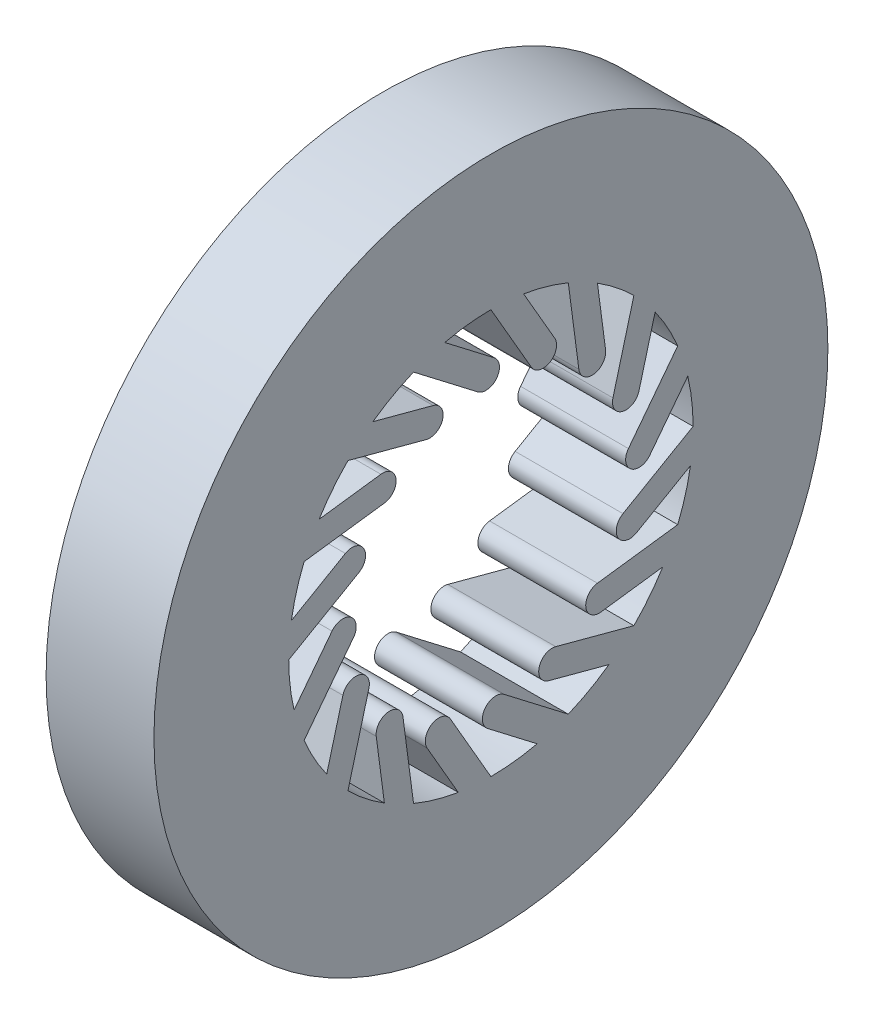
SolidWorks part; units mm, degrees
material "ABS"
ref_plane "Front Plane" through (0, 0, 0) normal (0, 0, 1) x (1, 0, 0)
ref_plane "Top Plane" through (0, 0, 0) normal (0, 1, 0) x (1, 0, 0)
ref_plane "Right Plane" through (0, 0, 0) normal (1, 0, 0) x (0, 0, -1)
sketch "Sketch1" plane through (0, 0, 0) normal (1, 0, 0) x (0, 0, -1)
  line L0 (0, 15) -> (3.0041, 9.7967)
  line L1 (0, -1000) -> (0, 49000) construction
  line L2 (4.7362, 10.7967) -> (2.4231, 14.803)
  line L3 (8.5074, 8.1624) -> (7.9036, 12.7489)
  line L4 (5.7403, 13.8582) -> (6.5245, 7.9013)
  line L5 (10.9834, 4.2854) -> (12.1807, 8.7539)
  line L6 (10.6066, 10.6066) -> (9.0515, 4.8031)
  line L7 (11.7873, -0.2439) -> (14.6035, 3.4262)
  line L8 (13.8582, 5.7403) -> (10.2006, 0.9736)
  line L9 (10.7967, -4.7362) -> (14.803, -2.4231)
  line L10 (15, 0) -> (9.7967, -3.0041)
  line L11 (8.1624, -8.5074) -> (12.7489, -7.9036)
  line L12 (13.8582, -5.7403) -> (7.9013, -6.5245)
  line L13 (4.2854, -10.9834) -> (8.7539, -12.1807)
  line L14 (10.6066, -10.6066) -> (4.8031, -9.0515)
  line L15 (-0.2439, -11.7873) -> (3.4262, -14.6035)
  line L16 (5.7403, -13.8582) -> (0.9736, -10.2006)
  line L17 (-4.7362, -10.7967) -> (-2.4231, -14.803)
  line L18 (0, -15) -> (-3.0041, -9.7967)
  line L19 (-8.5074, -8.1624) -> (-7.9036, -12.7489)
  line L20 (-5.7403, -13.8582) -> (-6.5245, -7.9013)
  line L21 (-10.9834, -4.2854) -> (-12.1807, -8.7539)
  line L22 (-10.6066, -10.6066) -> (-9.0515, -4.8031)
  line L23 (-11.7873, 0.2439) -> (-14.6035, -3.4262)
  line L24 (-13.8582, -5.7403) -> (-10.2006, -0.9736)
  line L25 (-10.7967, 4.7362) -> (-14.803, 2.4231)
  line L26 (-15, 0) -> (-9.7967, 3.0041)
  line L27 (-8.1624, 8.5074) -> (-12.7489, 7.9036)
  line L28 (-13.8582, 5.7403) -> (-7.9013, 6.5245)
  line L29 (-4.2854, 10.9834) -> (-8.7539, 12.1807)
  line L30 (-10.6066, 10.6066) -> (-4.8031, 9.0515)
  line L31 (0.2439, 11.7873) -> (-3.4262, 14.6035)
  line L32 (-5.7403, 13.8582) -> (-0.9736, 10.2006)
  circle A0 centre (0, 0) radius 10 construction
  arc A1 (-10.6066, 10.6066) -> (-12.7489, 7.9036) centre (0, 0) ccw
  arc A2 (3.0041, 9.7967) -> (4.7362, 10.7967) centre (3.8702, 10.2967) ccw
  circle A3 centre (0, 0) radius 11.7898 construction
  arc A4 (6.5245, 7.9013) -> (8.5074, 8.1624) centre (7.5159, 8.0319) ccw
  arc A5 (9.0515, 4.8031) -> (10.9834, 4.2854) centre (10.0175, 4.5442) ccw
  arc A6 (10.2006, 0.9736) -> (11.7873, -0.2439) centre (10.9939, 0.3648) ccw
  arc A7 (9.7967, -3.0041) -> (10.7967, -4.7362) centre (10.2967, -3.8702) ccw
  arc A8 (7.9013, -6.5245) -> (8.1624, -8.5074) centre (8.0319, -7.5159) ccw
  arc A9 (4.8031, -9.0515) -> (4.2854, -10.9834) centre (4.5442, -10.0175) ccw
  arc A10 (0.9736, -10.2006) -> (-0.2439, -11.7873) centre (0.3648, -10.9939) ccw
  arc A11 (-3.0041, -9.7967) -> (-4.7362, -10.7967) centre (-3.8702, -10.2967) ccw
  arc A12 (-6.5245, -7.9013) -> (-8.5074, -8.1624) centre (-7.5159, -8.0319) ccw
  arc A13 (-9.0515, -4.8031) -> (-10.9834, -4.2854) centre (-10.0175, -4.5442) ccw
  arc A14 (-10.2006, -0.9736) -> (-11.7873, 0.2439) centre (-10.9939, -0.3648) ccw
  arc A15 (-9.7967, 3.0041) -> (-10.7967, 4.7362) centre (-10.2967, 3.8702) ccw
  arc A16 (-7.9013, 6.5245) -> (-8.1624, 8.5074) centre (-8.0319, 7.5159) ccw
  arc A17 (-4.8031, 9.0515) -> (-4.2854, 10.9834) centre (-4.5442, 10.0175) ccw
  arc A18 (-0.9736, 10.2006) -> (0.2439, 11.7873) centre (-0.3648, 10.9939) ccw
  circle A19 centre (0, 0) radius 25
  arc A20 (-13.8582, 5.7403) -> (-14.803, 2.4231) centre (0, 0) ccw
  arc A21 (-15, 0) -> (-14.6035, -3.4262) centre (0, 0) ccw
  arc A22 (-13.8582, -5.7403) -> (-12.1807, -8.7539) centre (0, 0) ccw
  arc A23 (-10.6066, -10.6066) -> (-7.9036, -12.7489) centre (0, 0) ccw
  arc A24 (-5.7403, -13.8582) -> (-2.4231, -14.803) centre (0, 0) ccw
  arc A25 (0, -15) -> (3.4262, -14.6035) centre (0, 0) ccw
  arc A26 (5.7403, -13.8582) -> (8.7539, -12.1807) centre (0, 0) ccw
  arc A27 (10.6066, -10.6066) -> (12.7489, -7.9036) centre (0, 0) ccw
  arc A28 (13.8582, -5.7403) -> (14.803, -2.4231) centre (0, 0) ccw
  arc A29 (15, 0) -> (14.6035, 3.4262) centre (0, 0) ccw
  arc A30 (13.8582, 5.7403) -> (12.1807, 8.7539) centre (0, 0) ccw
  arc A31 (10.6066, 10.6066) -> (7.9036, 12.7489) centre (0, 0) ccw
  arc A32 (5.7403, 13.8582) -> (2.4231, 14.803) centre (0, 0) ccw
  arc A33 (0, 15) -> (-3.4262, 14.6035) centre (0, 0) ccw
  arc A34 (-5.7403, 13.8582) -> (-8.7539, 12.1807) centre (0, 0) ccw
  point P90 (0, 0)
  dimension "D1" = 20
  dimension "D2" = 30
  dimension "D3" = 2
  dimension "D4" = 30
  dimension "D5" = 16
  dimension "D6" = 50
extrude "Magnet ring" add sketch "Sketch1" along normal blind 8
